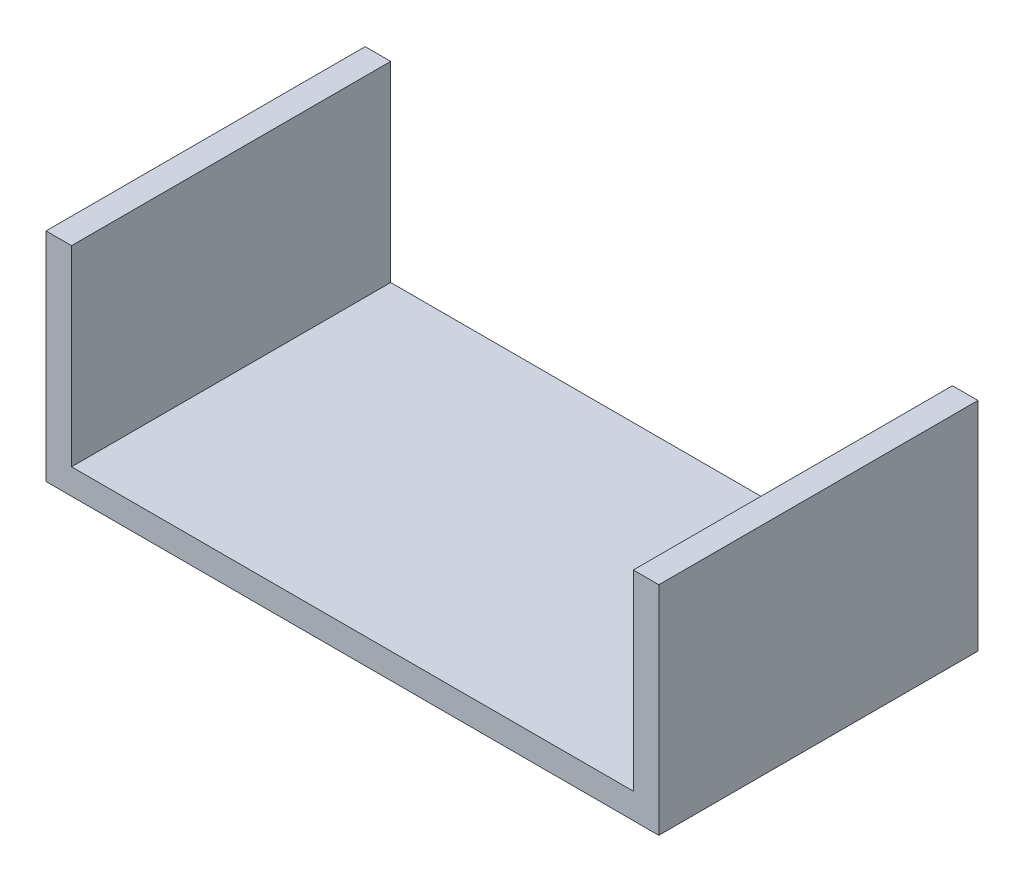
SolidWorks part; units mm, degrees
ref_plane "Plano frontal" through (0, 0, 0) normal (0, 0, 1) x (1, 0, 0)
ref_plane "Plano superior" through (0, 0, 0) normal (0, 1, 0) x (1, 0, 0)
ref_plane "Plano direito" through (0, 0, 0) normal (1, 0, 0) x (0, 0, -1)
sketch "Esboço1" plane through (0, 0, 0) normal (0, 1, 0) x (1, 0, 0)
  line L1 (-24, -12.5) -> (24, -12.5)
  line L2 (-24, -12.5) -> (-24, 12.5)
  line L3 (-24, 12.5) -> (24, 12.5)
  line L4 (24, -12.5) -> (24, 12.5)
  line L5 (-24, -12.5) -> (24, 12.5) construction
  line L6 (-24, 12.5) -> (24, -12.5) construction
  point P0 (0, 0)
  dimension "D1" = 48
  dimension "D2" = 25
extrude "Ressalto-extrusão1" add sketch "Esboço1" along normal mid plane 17
shell "Casca1" thickness 2
